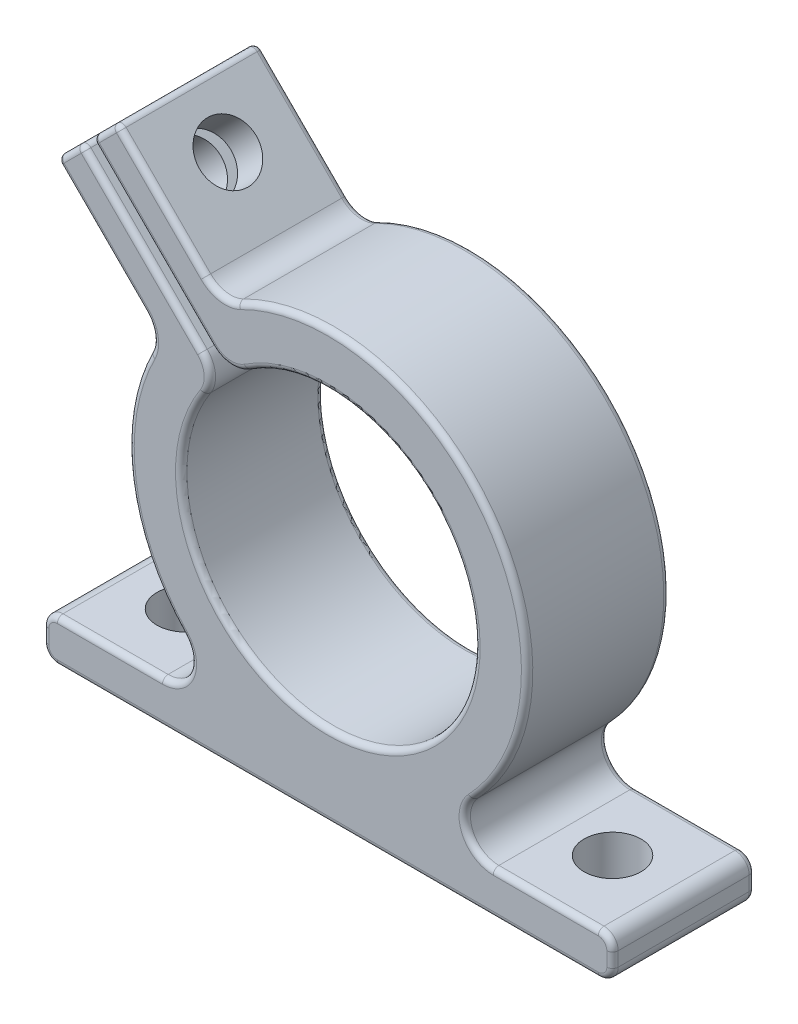
SolidWorks part; units mm, degrees
ref_plane "前视基准面" through (0, 0, 0) normal (0, 0, 1) x (1, 0, 0)
ref_plane "上视基准面" through (0, 0, 0) normal (0, 1, 0) x (1, 0, 0)
ref_plane "右视基准面" through (0, 0, 0) normal (1, 0, 0) x (0, 0, -1)
sketch "草图1" plane through (0, 0, 0) normal (0, 0, 1) x (1, 0, 0)
  line L0 (-9.5, -6.5) -> (-5.8095, -6.5)
  line L1 (-9.5, -8) -> (9.5, -8)
  line L2 (-10, -7) -> (-10, -7.5)
  line L3 (10, -7) -> (10, -7.5)
  line L4 (9.5, -6.5) -> (5.8095, -6.5)
  line L5 (0, 0) -> (-8.4853, 8.4853) construction
  line L6 (-7.2832, 9.4045) -> (-4.3129, 6.4342)
  line L7 (-8.8035, 8.1671) -> (-9.4045, 7.566)
  line L8 (0, 0) -> (0, -2.1091) construction
  line L9 (-8.1671, 8.5206) -> (-4.0812, 4.4347)
  line L10 (-8.1671, 8.8035) -> (-7.566, 9.4045)
  line L11 (-9.4045, 7.2832) -> (-6.4342, 4.3129)
  line L13 (-8.5206, 8.1671) -> (-4.4347, 4.0812)
  line L14 (0, 0) -> (0, -15.0845) construction
  arc A0 (-4.3057, 2.8254) -> (-2.8254, 4.3057) centre (0, 0) ccw
  arc A1 (-6.2486, 3.1551) -> (-5.0833, -4.8125) centre (0, 0) ccw
  arc A2 (10, -7) -> (9.5, -6.5) centre (9.5, -7) ccw
  arc A3 (-5.0833, -4.8125) -> (-5.8095, -6.5) centre (-5.8095, -5.5) cw
  arc A4 (9.5, -8) -> (10, -7.5) centre (9.5, -7.5) ccw
  arc A5 (5.0833, -4.8125) -> (5.8095, -6.5) centre (5.8095, -5.5) ccw
  arc A6 (-9.5, -8) -> (-10, -7.5) centre (-9.5, -7.5) cw
  arc A7 (-10, -7) -> (-9.5, -6.5) centre (-9.5, -7) cw
  arc A8 (5.0833, -4.8125) -> (-3.1551, 6.2486) centre (0, 0) ccw
  arc A9 (-8.1671, 8.8035) -> (-8.1671, 8.5206) centre (-8.0257, 8.6621) ccw
  arc A10 (-7.2832, 9.4045) -> (-7.566, 9.4045) centre (-7.4246, 9.2631) ccw
  arc A11 (-4.3129, 6.4342) -> (-3.1551, 6.2486) centre (-3.6058, 7.1413) ccw
  arc A12 (-4.0812, 4.4347) -> (-2.8254, 4.3057) centre (-3.3741, 5.1418) ccw
  arc A13 (-9.4045, 7.2832) -> (-9.4045, 7.566) centre (-9.2631, 7.4246) cw
  arc A14 (-8.8035, 8.1671) -> (-8.5206, 8.1671) centre (-8.6621, 8.0257) cw
  arc A15 (-6.4342, 4.3129) -> (-6.2486, 3.1551) centre (-7.1413, 3.6058) cw
  arc A16 (-4.4347, 4.0812) -> (-4.3057, 2.8254) centre (-5.1418, 3.3741) cw
  point P13 (2.5981, -6.5)
  point P19 (0, -8)
  point P36 (-0.3, 12)
  dimension "D1" = 6.5
  dimension "D9" = 0.2
  dimension "D10" = 1
  dimension "D5" = 1.5
  dimension "D8" = 0.2
  dimension "D2" = 1.5
  dimension "D6" = 0.25
  dimension "D7" = 12
extrude "凸台-拉伸1" add sketch "草图1" along normal blind 5
sketch "草图3" plane through (0, -6.5, 0) normal (0, 1, 0) x (1, 0, 0)
  circle A0 centre (-7.5, -2.5) radius 1
  circle A1 centre (7.5, -2.5) radius 1
extrude "切除-拉伸1" cut sketch "草图3" against normal up to next
fillet "圆角2" radius 0.2 56 edges at (5.614, 4.1813, 0) (-4.8909, -5.8953, 0) (-7.6547, -6.5, 0) (-9.8536, -6.6464, 0) (-10, -7.25, 0) (-9.8536, -7.8536, 0) (0, -8, 0) (0, -8, 5) (-9.8536, -7.8536, 5) (-10, -7.25, 5) (-9.8536, -6.6464, 5) (-7.6547, -6.5, 5) (-4.8909, -5.8953, 5) (5.614, 4.1813, 5) (3.6416, -3.6416, 5) (3.6416, -3.6416, 0) (-6.9263, -1.0131, 5) (-6.1539, 3.764, 5) (-7.9194, 5.798, 5) (-9.4631, 7.4246, 5) (-9.104, 7.8666, 5) (-8.6621, 8.2257, 5) (-6.4777, 6.1241, 5) (-4.147, 3.4762, 5) (-3.4762, 4.147, 5) (-6.1241, 6.4777, 5) (-8.2257, 8.6621, 5) (-7.8666, 9.104, 5) (-7.4246, 9.4631, 5) (-5.798, 7.9194, 5) (-3.764, 6.1539, 5) (-3.764, 6.1539, 0) (-5.798, 7.9194, 0) (-7.4246, 9.4631, 0) (-7.8666, 9.104, 0) (-8.2257, 8.6621, 0) (-6.1241, 6.4777, 0) (-3.4762, 4.147, 0) (-4.147, 3.4762, 0) (-6.4777, 6.1241, 0) (-8.6621, 8.2257, 0) (-9.104, 7.8666, 0) (-9.4631, 7.4246, 0) (-7.9194, 5.798, 0) (-6.1539, 3.764, 0) (-6.9263, -1.0131, 0) (7.6547, -6.5, 5) (9.8536, -6.6464, 5) (10, -7.25, 5) (9.8536, -7.8536, 5) (4.8909, -5.8953, 5) (9.8536, -7.8536, 0) (10, -7.25, 0) (9.8536, -6.6464, 0) (7.6547, -6.5, 0) (4.8909, -5.8953, 0)
sketch "草图5" plane through (-1.0607, -1.0607, 0) normal (-0.7071, -0.7071, 0) x (0, 0, 1)
  circle A0 centre (2.5, 10) radius 1
extrude "切除-拉伸3" cut sketch "草图5" against normal blind 10
